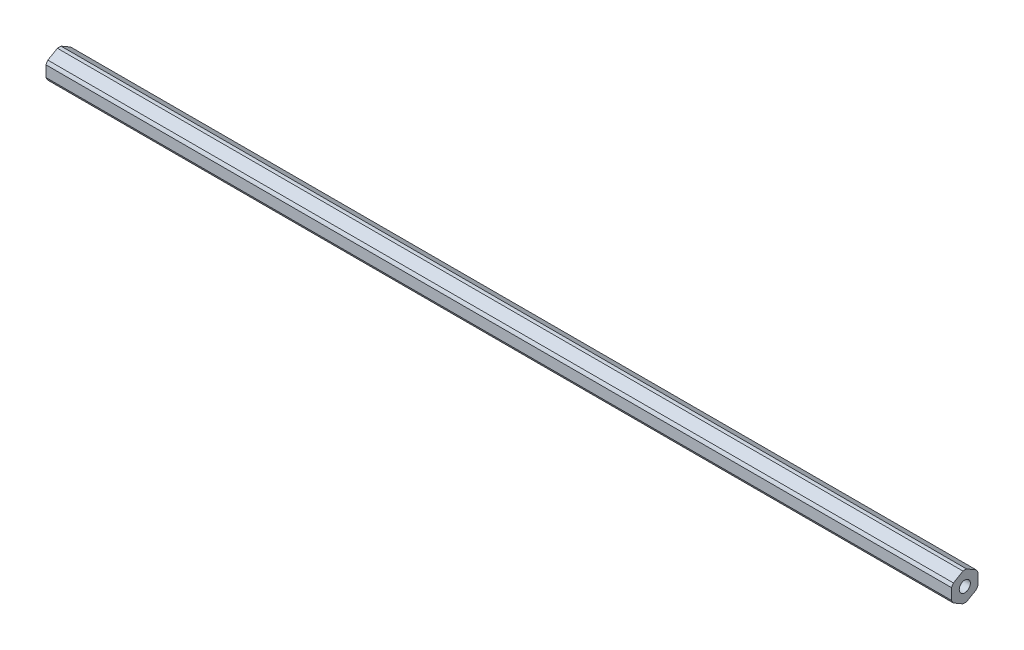
SolidWorks part; units mm, degrees
ref_plane "Front Plane" through (0, 0, 0) normal (0, 0, 1) x (1, 0, 0)
ref_plane "Top Plane" through (0, 0, 0) normal (0, 1, 0) x (1, 0, 0)
ref_plane "Right Plane" through (0, 0, 0) normal (1, 0, 0) x (0, 0, -1)
ref_plane "Plane1" through (244.475, 0, 0) normal (1, 0, 0) x (0, 0, -1)
sketch "Sketch1" plane through (244.475, 0, 0) normal (1, 0, 0) x (0, 0, -1)
  line L0 (5.4682, 4.1753) -> (0.8818, 6.8233)
  line L1 (-0.8818, 6.8233) -> (-5.4682, 4.1753)
  line L2 (-6.35, 2.648) -> (-6.35, -2.648)
  line L3 (-5.4682, -4.1753) -> (-0.8818, -6.8233)
  line L4 (0.8818, -6.8233) -> (5.4682, -4.1753)
  line L5 (6.35, -2.648) -> (6.35, 2.648)
  circle A0 centre (0, 0) radius 2.667
  arc A1 (6.35, 2.648) -> (5.4682, 4.1753) centre (0, 0) ccw
  arc A2 (0.8818, 6.8233) -> (-0.8818, 6.8233) centre (0, 0) ccw
  arc A3 (-5.4682, 4.1753) -> (-6.35, 2.648) centre (0, 0) ccw
  arc A4 (-6.35, -2.648) -> (-5.4682, -4.1753) centre (0, 0) ccw
  arc A5 (-0.8818, -6.8233) -> (0.8818, -6.8233) centre (0, 0) ccw
  arc A6 (5.4682, -4.1753) -> (6.35, -2.648) centre (0, 0) ccw
extrude "Boss-Extrude1" add sketch "Sketch1" against normal blind 435.102
